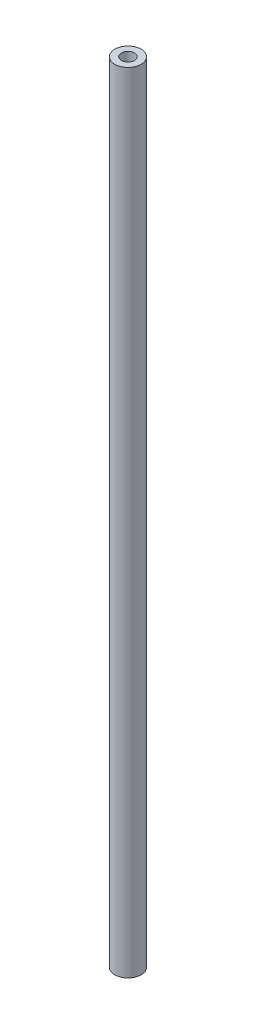
SolidWorks part; units mm, degrees
ref_plane "Front Plane" through (0, 0, 0) normal (0, 0, 1) x (1, 0, 0)
ref_plane "Top Plane" through (0, 0, 0) normal (0, 1, 0) x (1, 0, 0)
ref_plane "Right Plane" through (0, 0, 0) normal (1, 0, 0) x (0, 0, -1)
sketch "Sketch1" plane through (0, 0, 0) normal (0, 1, 0) x (1, 0, 0)
  circle A0 centre (0, 0) radius 6.35
  circle A1 centre (0, 0) radius 3.175
  dimension "D1" = 12.7
  dimension "D2" = 6.35
extrude "Boss-Extrude1" add sketch "Sketch1" along normal blind 381
